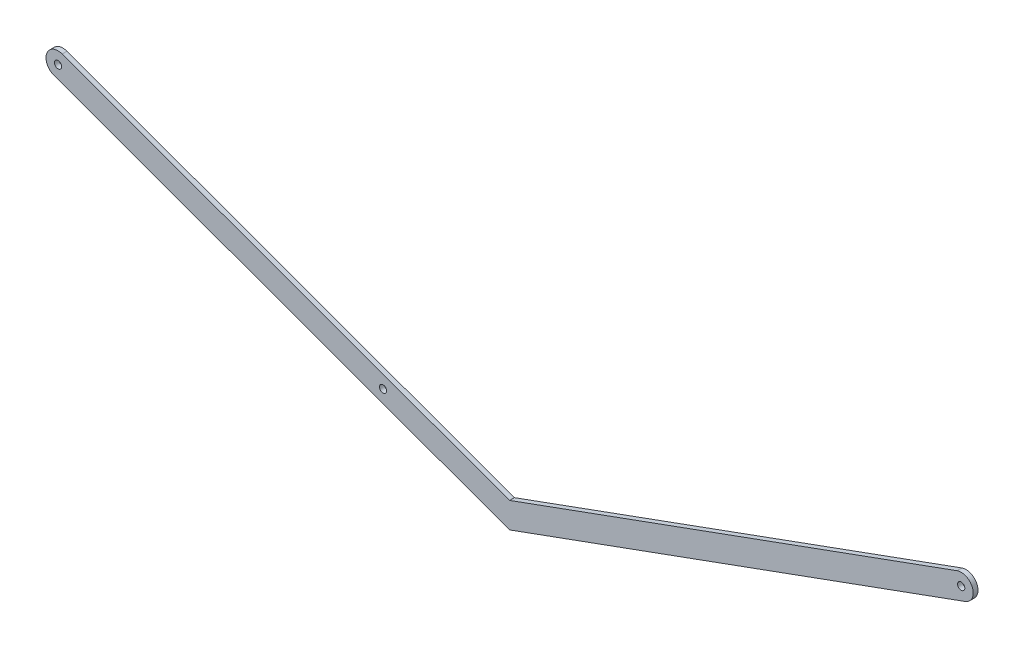
SolidWorks part; units mm, degrees
material "Plain Carbon Steel"
ref_plane "Front Plane" through (0, 0, 0) normal (0, 0, 1) x (1, 0, 0)
ref_plane "Top Plane" through (0, 0, 0) normal (0, 1, 0) x (1, 0, 0)
ref_plane "Right Plane" through (0, 0, 0) normal (1, 0, 0) x (0, 0, -1)
sketch "Sketch1" plane through (0, 0, 0) normal (0, 0, 1) x (1, 0, 0)
  line L0 (596.9, 0) -> (-596.9, 0) construction
  line L1 (3.4925, 0) -> (-3.4925, 0) construction
  line L4 (-602.3296, -14.9176) -> (0, -234.1477)
  line L5 (0, -234.1477) -> (602.3296, -14.9176)
  line L7 (0, -3.4925) -> (0, 3.4925) construction
  line L8 (-591.4704, 14.9176) -> (0, -200.36)
  line L9 (0, -200.36) -> (591.4704, 14.9176)
  line L10 (-596.9, 0) -> (-167.2725, -156.3716) construction
  arc A0 (602.3296, -14.9176) -> (591.4704, 14.9176) centre (596.9, 0) ccw
  arc A1 (-591.4704, 14.9176) -> (-602.3296, -14.9176) centre (-596.9, 0) ccw
  circle A2 centre (-596.9, 0) radius 4.7625
  circle A3 centre (596.9, 0) radius 4.7625
  circle A4 centre (-167.2725, -156.3716) radius 4.7625
  point P5 (0, 0)
  dimension "D4" = 9.525
  dimension "D5" = 9.525
  dimension "D6" = 457.2
  dimension "D1" = 31.75
  dimension "D2" = 1193.8
  dimension "D3" = 140
extrude "Boss-Extrude1" add sketch "Sketch1" along normal mid plane 6.35
